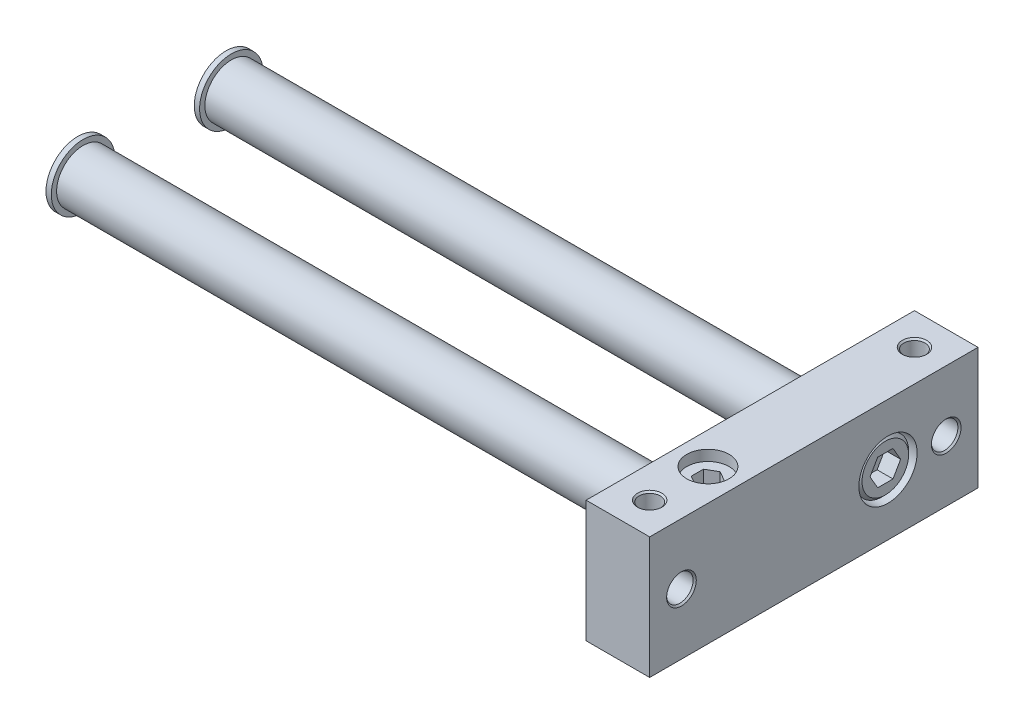
SolidWorks part; units mm, degrees
ref_plane "Plane1" through (0, 0, 0) normal (0, 0, 1) x (1, 0, 0)
ref_plane "Plane2" through (0, 0, 0) normal (0, 1, 0) x (1, 0, 0)
ref_plane "Plane3" through (0, 0, 0) normal (1, 0, 0) x (0, 0, -1)
sketch "Plate_Sketch" plane through (0, 0, 0) normal (1, 0, 0) x (0, 0, -1)
  line L0 (-31, 11.5) -> (-31, -11.5)
  line L1 (-31, -11.5) -> (31, -11.5)
  line L2 (31, -11.5) -> (31, 11.5)
  line L3 (31, 11.5) -> (-31, 11.5)
  line L4 (-24.2, 0) -> (24.2, 0) construction
  line L5 (0, -6.75) -> (0, 9.75) construction
  line L6 (0, 12.5779) -> (0, -12.5779) construction
  line L7 (16.4357, 0) -> (-16.4357, 0) construction
  dimension "C" = 62
  dimension "D" = 23
extrude "Plate" add sketch "Plate_Sketch" along normal blind 12
hole_wizard "Tapped Hole Face" positions "Tapped Hole Face Loc" profile "Tapped Hole Face Profile" tap size "M3x0.5" standard "Ansi Metric" end condition through all
sketch "Tapped Hole Face Loc" plane through (12, 0, 0) normal (1, 0, 0) x (0, 0, -1)
  line L0 (0, 0) -> (0, 21.0226) construction
  line L1 (-31, -11.5) -> (31, -11.5) construction
  point P0 (-25, 0)
  point P1 (25, 0)
  dimension "G" = 50
  dimension "E" = 11.5
sketch "Tapped Hole Face Profile" plane through (12, 0, 25) normal (0, 1, 0) x (0, 0, -1)
  line L0 (0, 0) -> (0, 12)
  line L1 (0, 12) -> (2.5, 12)
  line L2 (2.5, 12) -> (2.5, 0.3)
  line L3 (2.5, 0.3) -> (2.8, 0)
  line L5 (2.8, 0) -> (0, 0)
  line L6 (-2.5, 0.3) -> (-2.8, 0) construction
  line L11 (0, -6.35) -> (0, 107.95) construction
  dimension "Thread Major Dia." = 5
  dimension "Thru Tap Drill Depth" = 12
  dimension "Near CSink Dia." = 5.6
  dimension "Near CSink Angle" = 90
ref_plane "bottom" through (0, -12.5, 0) normal (0, -1, 0) x (1, 0, 0)
ref_plane "innerlimit" through (-12, 0, 0) normal (1, 0, 0) x (0, 0, -1)
ref_plane "strokelimit" through (-102, 0, 0) normal (1, 0, 0) x (0, 0, -1)
sketch "Rods_Sketch" plane through (-12, 0, 0) normal (-1, 0, 0) x (0, 0, 1)
  line L0 (0, -7.7893) -> (0, 7.4105) construction
  line L1 (0, -12.5779) -> (0, 12.5779) construction
  line L3 (-4, -12.5) -> (4, -12.5) construction
  circle A0 centre (-14, 0) radius 5
  circle A1 centre (14, 0) radius 5
  dimension "NN" = 10
  dimension "H" = 28
  dimension "QQ" = 12.5
extrude "Rods" add sketch "Rods_Sketch" along normal blind 100 and the other way up to surface (24 mm away)
sketch "Piston_Sketch" plane through (-112, 0, 0) normal (-1, 0, 0) x (0, 0, 1)
  circle A0 centre (-14, 0) radius 6
  circle A1 centre (14, 0) radius 6
extrude "Piston" add sketch "Piston_Sketch" along normal blind 1
hole_wizard "Tapped Holes Top" positions "Tapped Holes Top Loc" profile "Tapped Holes Top Profile" tap size "M3x0.5" standard "Ansi Metric"
sketch "Tapped Holes Top Loc" plane through (0, 11.5, 0) normal (0, 1, 0) x (-1, 0, 0)
  line L0 (0, 0) -> (-11.3574, 0) construction
  line L2 (-12, -31) -> (-12, 31) construction
  line L3 (0, -25) -> (-11.7, -25) construction
  point P0 (-6, -25)
  point P1 (-6, 25)
  dimension "I" = 6
sketch "Tapped Holes Top Profile" plane through (6, 11.5, -25) normal (1, 0, 0) x (0, 0, 1)
  line L0 (0, 0) -> (0, 6.4998)
  line L1 (0, 6.4998) -> (1.7, 6.2)
  line L2 (1.7, 6.2) -> (1.7, 6)
  line L3 (1.7, 6) -> (2, 6)
  line L5 (2, 6) -> (2, 0.3)
  line L6 (2, 0.3) -> (2.3, 0)
  line L7 (2.3, 0) -> (0, 0)
  line L8 (-2, 0.3) -> (-2.3, 0) construction
  line L10 (0, 6.4998) -> (-1.7, 6.2) construction
  line L11 (0, -6.35) -> (0, 107.95) construction
  dimension "Tap Drill Dia." = 3.4
  dimension "Tap Drill Depth" = 6.2
  dimension "Thread Major Dia." = 4
  dimension "Thread Depth" = 6
  dimension "Near C'Sink Dia." = 4.6
  dimension "Near C'Sink Angle" = 90
  dimension "Drill Angle" = 160
mirror "Tapped Holes Top Mirror" about plane through (0, 0, 0) normal (0, 1, 0) of "Tapped Holes Top"
sketch "SHCS Seat_Sketch" plane through (12, 0, 0) normal (1, 0, 0) x (0, 0, -1)
  circle A0 centre (14, 0) radius 5.5
  circle A1 centre (14, 0) radius 5 construction
  dimension "Dia" = 11
extrude "SHCS Seat" cut sketch "SHCS Seat_Sketch" against normal blind 6.5
sketch "SHCS Head_Sketch" plane through (5.5, 0, 0) normal (1, 0, 0) x (0, 0, -1)
  circle A0 centre (14, 0) radius 5
  circle A1 centre (14, 0) radius 5.5 construction
  dimension "Dia" = 10
extrude "SHCS Head" add sketch "SHCS Head_Sketch" along normal blind 6
sketch "SHCS Hex_Sketch" plane through (11.5, 0, 0) normal (1, 0, 0) x (0, 0, -1)
  line L1 (15.4434, -2.5) -> (16.8868, 0)
  line L2 (16.8868, 0) -> (15.4434, 2.5)
  line L3 (15.4434, 2.5) -> (12.5566, 2.5)
  line L4 (12.5566, 2.5) -> (11.1132, 0)
  line L5 (11.1132, 0) -> (12.5566, -2.5)
  line L6 (12.5566, -2.5) -> (15.4434, -2.5)
  circle A0 centre (14, 0) radius 2.5 construction
  circle A1 centre (14, 0) radius 5 construction
  dimension "Flats" = 5
extrude "SHCS Hex" cut sketch "SHCS Hex_Sketch" against normal blind 3
chamfer "SHCS Cham" distance 0.6 1 edges at (11.5, 0, -19)
sketch "SS Seat_Sketch" plane through (0, 11.5, 0) normal (0, 1, 0) x (-1, 0, 0)
  line L0 (112, 14) -> (0, 14) construction
  circle A0 centre (-6, 14) radius 4
  dimension "Dia" = 8
extrude "SS Seat" cut sketch "SS Seat_Sketch" against normal blind 2
sketch "SS Hex_Sketch" plane through (0, 9.5, 0) normal (0, 1, 0) x (-1, 0, 0)
  line L1 (-8, 12.8453) -> (-6, 11.6906)
  line L2 (-6, 11.6906) -> (-4, 12.8453)
  line L3 (-4, 12.8453) -> (-4, 15.1547)
  line L4 (-4, 15.1547) -> (-6, 16.3094)
  line L5 (-6, 16.3094) -> (-8, 15.1547)
  line L6 (-8, 15.1547) -> (-8, 12.8453)
  circle A0 centre (-6, 14) radius 2 construction
  circle A1 centre (-6, 14) radius 4 construction
  dimension "Flats" = 4
extrude "SS Hex" cut sketch "SS Hex_Sketch" against normal blind 4
